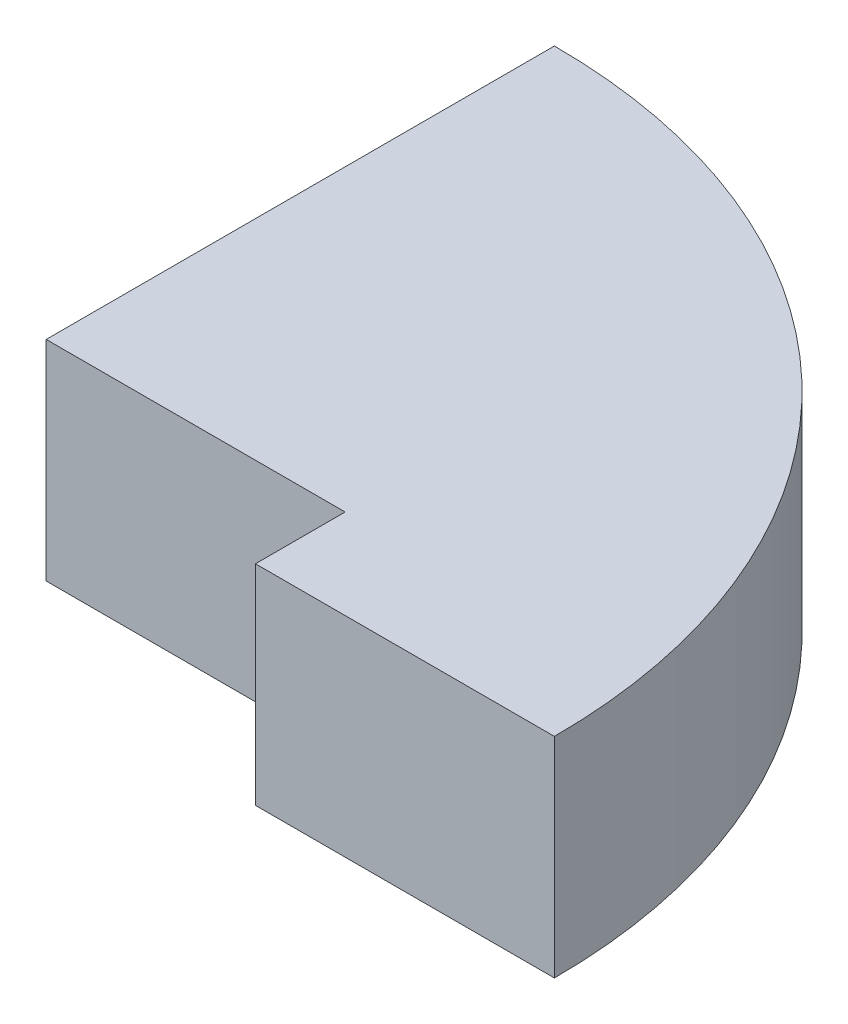
SolidWorks part; units mm, degrees
material "Plain Carbon Steel"
ref_plane "Front Plane" through (0, 0, 0) normal (0, 0, 1) x (1, 0, 0)
ref_plane "Top Plane" through (0, 0, 0) normal (0, 1, 0) x (1, 0, 0)
ref_plane "Right Plane" through (0, 0, 0) normal (1, 0, 0) x (0, 0, -1)
sketch "Sketch1" plane through (0, 0, 0) normal (0, 1, 0) x (1, 0, 0)
  line L0 (0, 0) -> (0, 63.5)
  line L1 (0, 0) -> (63.5, 0)
  line L3 (0, 0) -> (31.75, 0)
  line L4 (0, 0) -> (0, 9.525)
  line L5 (0, 9.525) -> (31.75, 9.525)
  line L6 (31.75, 0) -> (31.75, 9.525)
  arc A1 (63.5, 0) -> (0, 63.5) centre (0, 0) ccw
  dimension "D1" = 63.5
  dimension "D2" = 31.75
  dimension "D3" = 9.525
extrude "Boss-Extrude1" add sketch "Sketch1" along normal blind 22.225 contours L1 A1 L0 L5 L6
